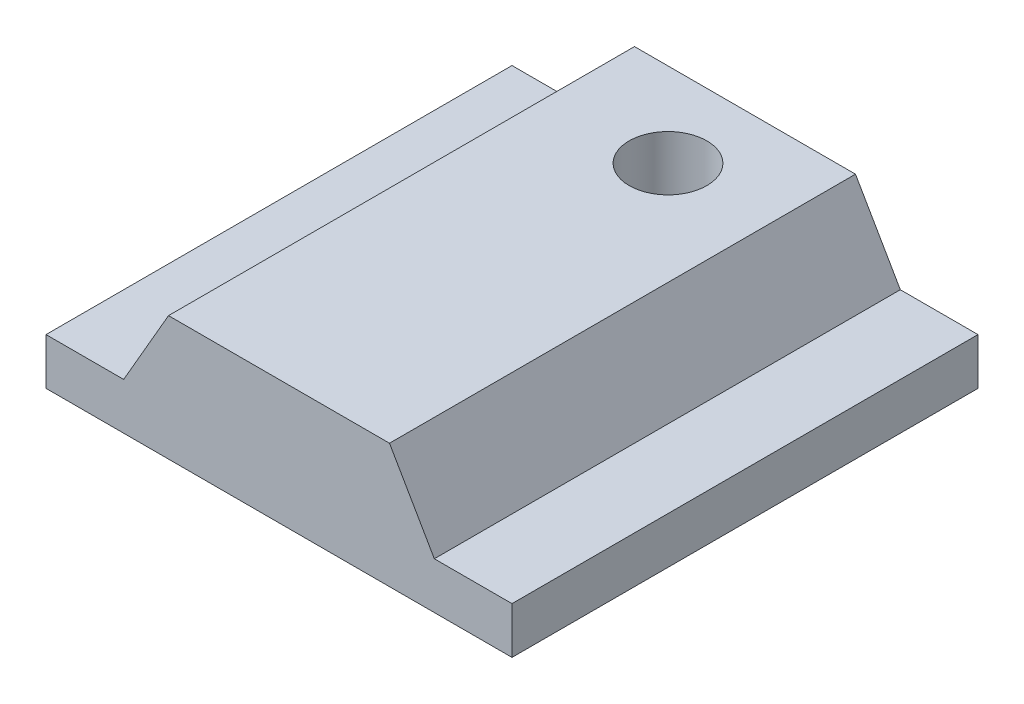
SolidWorks part; units mm, degrees
ref_plane "Спереди" through (0, 0, 0) normal (0, 0, 1) x (1, 0, 0)
ref_plane "Сверху" through (0, 0, 0) normal (0, 1, 0) x (1, 0, 0)
ref_plane "Справа" through (0, 0, 0) normal (1, 0, 0) x (0, 0, -1)
sketch "Эскиз1" plane through (0, 0, 0) normal (0, 0, 1) x (1, 0, 0)
  line L0 (0, 0) -> (0, 8)
  line L1 (0, 8) -> (30, 8)
  line L2 (30, 8) -> (30, 0)
  line L3 (30, 0) -> (0, 0)
  dimension "D1" = 30
  dimension "D2" = 8
extrude "Бобышка-Вытянуть1" add sketch "Эскиз1" along normal blind 30
sketch "Эскиз2" plane through (0, 0, 30) normal (0, 0, 1) x (1, 0, 0)
  line L0 (7.3094, 8) -> (5, 4)
  line L1 (30, 8) -> (0, 8) construction
  line L2 (5, 4) -> (25, 4)
  line L3 (25, 4) -> (22.6906, 8)
  line L4 (22.6906, 8) -> (7.3094, 8)
  line L5 (30, 0) -> (30, 8) construction
  dimension "D1" = 4
  dimension "D2" = 60
  dimension "D3" = 60
  dimension "D4" = 20
  dimension "D5" = 5
extrude "Вырез-Вытянуть1" [suppressed] cut sketch "Эскиз2" against normal through all
sketch "Эскиз3" plane through (0, 0, 30) normal (0, 0, 1) x (1, 0, 0)
  line L0 (5, 3) -> (7.8868, 8)
  line L2 (30, 8) -> (0, 8) construction
  line L3 (7.8868, 8) -> (5, 8)
  line L4 (25, 3) -> (30, 3)
  line L5 (15, 8) -> (15, 1.7771) construction
  line L7 (25, 3) -> (22.1132, 8)
  line L8 (22.1132, 8) -> (25, 8)
  line L9 (5, 3) -> (0, 3)
  line L10 (0, 8) -> (0, 0) construction
  line L11 (0, 3) -> (0, 8)
  line L12 (0, 8) -> (5, 8)
  line L13 (30, 0) -> (30, 8) construction
  line L14 (30, 3) -> (30, 8)
  line L15 (30, 8) -> (25, 8)
  dimension "D1" = 60
  dimension "D2" = 5
  dimension "D3" = 20
extrude "Вырез-Вытянуть2" cut sketch "Эскиз3" against normal through all
hole_wizard "Отверстие обработанное метчиком M6x1.01" positions "Эскиз5" profile "Эскиз4" tap size "M6x1.0" standard "Ansi Metric"
sketch "Эскиз5" plane through (0, 8, 0) normal (0, 1, 0) x (1, 0, 0)
  point P0 (15.4685, -5.4252)
sketch "Эскиз4" plane through (15.4685, 8, 5.4252) normal (1, 0, 0) x (0, 0, 1)
  line L0 (0, 0) -> (0, 18.5022)
  line L1 (0, 18.5022) -> (2.5, 17)
  line L2 (2.5, 17) -> (2.5, 0)
  line L5 (2.5, 0) -> (0, 0)
  line L10 (0, 18.5022) -> (-2.5, 17) construction
  line L11 (0, -6.35) -> (0, 107.95) construction
  dimension "Диаметр сверла" = 5
  dimension "Глубина сверла" = 17
  dimension "Угол заточки сверла" = 118
cosmetic thread "Отверстие резьбы1" parameters "D1"=8, "D2"=6
